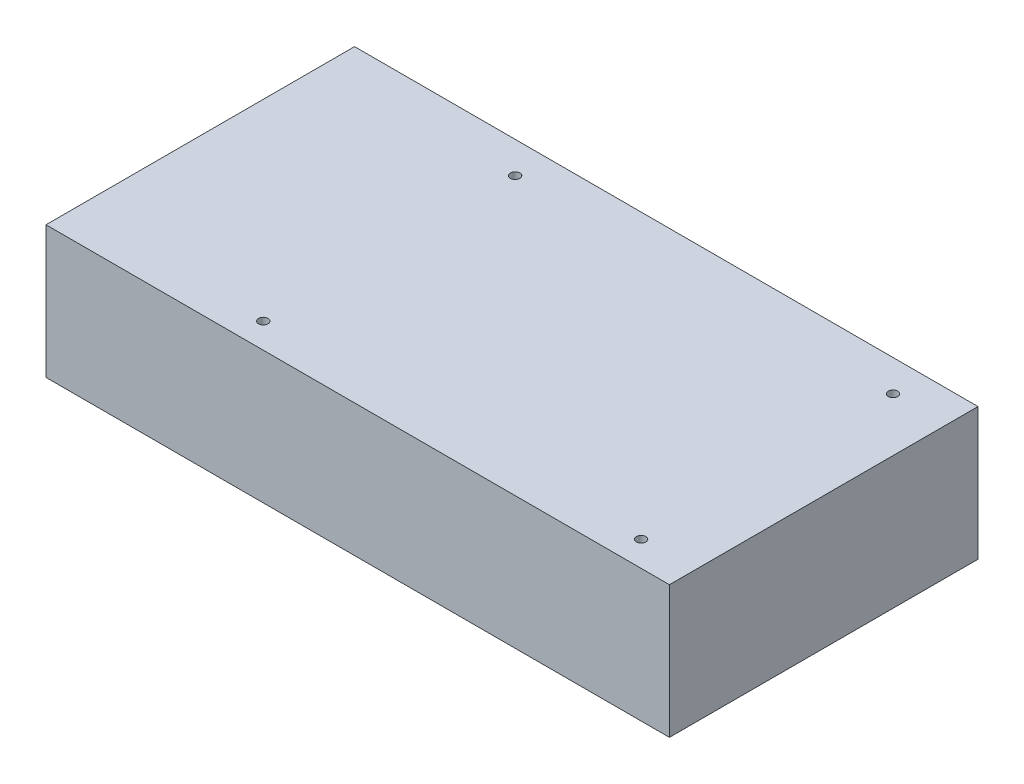
SolidWorks part; units mm, degrees
ref_plane "前视基准面" through (0, 0, 0) normal (0, 0, 1) x (1, 0, 0)
ref_plane "上视基准面" through (0, 0, 0) normal (0, 1, 0) x (1, 0, 0)
ref_plane "右视基准面" through (0, 0, 0) normal (1, 0, 0) x (0, 0, -1)
sketch "草图1" plane through (0, 0, 0) normal (0, 1, 0) x (1, 0, 0)
  line L1 (0, 0) -> (198, 0)
  line L2 (0, 0) -> (0, -98)
  line L3 (0, -98) -> (198, -98)
  line L4 (198, 0) -> (198, -98)
  dimension "D1" = 198
  dimension "D2" = 98
extrude "凸台-拉伸1" add sketch "草图1" along normal blind 42
sketch "草图2" plane through (0, 42, 0) normal (0, 1, 0) x (1, 0, 0)
  line L0 (0, -98) -> (198, -98) construction
  line L1 (61, -10) -> (181, -10) construction
  line L2 (61, -10) -> (61, -90) construction
  line L3 (61, -90) -> (181, -90) construction
  line L4 (181, -10) -> (181, -90) construction
  line L5 (61, -10) -> (181, -90) construction
  line L6 (61, -90) -> (181, -10) construction
  line L7 (198, -98) -> (198, 0) construction
  circle A0 centre (61, -10) radius 1.5
  circle A1 centre (181, -10) radius 1.5
  circle A2 centre (181, -90) radius 1.5
  circle A3 centre (61, -90) radius 1.5
  point P4 (121, -50)
  dimension "D1" = 3
  dimension "D2" = 3
  dimension "D3" = 3
  dimension "D4" = 3
  dimension "D5" = 120
  dimension "D6" = 80
  dimension "D7" = 8
  dimension "D8" = 17
extrude "切除-拉伸1" cut sketch "草图2" against normal blind 3
sketch "草图3" plane through (0, 0, 0) normal (0, -1, 0) x (1, 0, 0)
  line L0 (198, 98) -> (198, 0) construction
  line L2 (198, 0) -> (0, 0) construction
  circle A0 centre (153, 35) radius 28.5
  circle A1 centre (153, 35) radius 5
  point P7 (151.8349, 0)
  dimension "D1" = 57
  dimension "D4" = 10
  dimension "D2" = 45
  dimension "D3" = 35
extrude "切除-拉伸2" cut sketch "草图3" against normal blind 2
